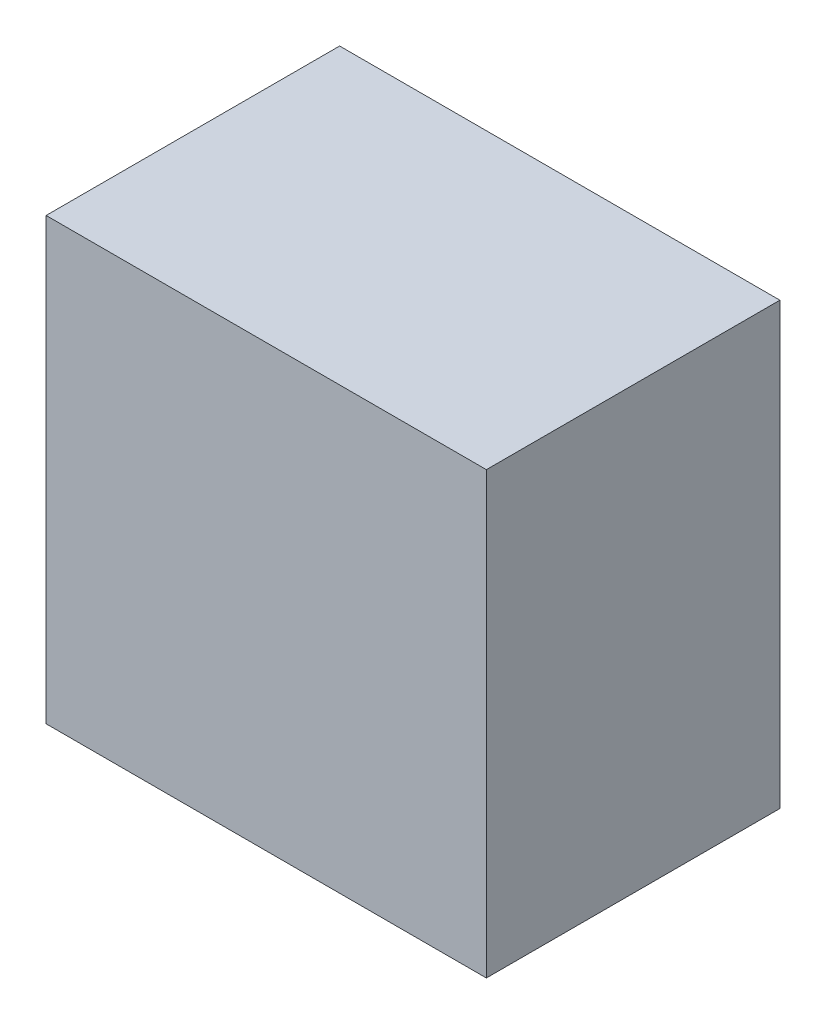
SolidWorks part; units mm, degrees
ref_plane "Front Plane" through (0, 0, 0) normal (0, 0, 1) x (1, 0, 0)
ref_plane "Top Plane" through (0, 0, 0) normal (0, 1, 0) x (1, 0, 0)
ref_plane "Right Plane" through (0, 0, 0) normal (1, 0, 0) x (0, 0, -1)
sketch "Sketch1" plane through (0, 0, 0) normal (0, 1, 0) x (1, 0, 0)
  line L1 (0, 0) -> (38.1, 0)
  line L2 (0, 0) -> (0, 25.4)
  line L3 (0, 25.4) -> (38.1, 25.4)
  line L4 (38.1, 0) -> (38.1, 25.4)
  dimension "D1" = 38.1
  dimension "D2" = 25.4
extrude "Boss-Extrude1" add sketch "Sketch1" along normal blind 38.1
sketch "Sketch2" plane through (0, 0, 0) normal (0, 0, 1) x (1, 0, 0)
  line L0 (0, 38.1) -> (38.1, 38.1) construction
  line L1 (38.1, 38.1) -> (38.1, 0) construction
  point P0 (25.4, 19.05)
  dimension "D1" = 19.05
  dimension "D2" = 12.7
sketch "Sketch3" plane through (0, 0, -25.4) normal (0, 0, -1) x (-1, 0, 0)
  line L0 (-38.1, 38.1) -> (0, 38.1) construction
  line L1 (-38.1, 38.1) -> (-38.1, 0) construction
  point P0 (-25.4, 19.05)
  dimension "D1" = 19.05
  dimension "D2" = 12.7
sketch "Sketch4" plane through (0, 0, 0) normal (-1, 0, 0) x (0, 0, 1)
  line L0 (-25.4, 38.1) -> (-25.4, 0) construction
  line L1 (-25.4, 38.1) -> (0, 38.1) construction
  point P0 (-12.7, 19.05)
  dimension "D1" = 12.7
  dimension "D2" = 19.05
sketch "Sketch5" plane through (38.1, 0, 0) normal (1, 0, 0) x (0, 0, -1)
  line L0 (0, 38.1) -> (25.4, 38.1) construction
  line L1 (0, 38.1) -> (0, 0) construction
  point P0 (12.7, 19.05)
  dimension "D1" = 19.05
  dimension "D2" = 12.7
